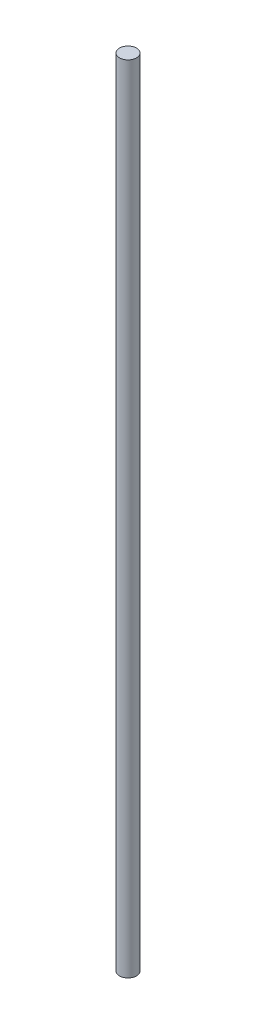
SolidWorks part; units mm, degrees
ref_plane "Plan de face" through (0, 0, 0) normal (0, 0, 1) x (1, 0, 0)
ref_plane "Plan de dessus" through (0, 0, 0) normal (0, 1, 0) x (1, 0, 0)
ref_plane "Plan de droite" through (0, 0, 0) normal (1, 0, 0) x (0, 0, -1)
sketch "Esquisse1" plane through (0, 0, 0) normal (0, 1, 0) x (1, 0, 0)
  circle A0 centre (0, 0) radius 3
  dimension "D1" = 6
extrude "Boss.-Extru.1" add sketch "Esquisse1" along normal blind 280 contours A0
